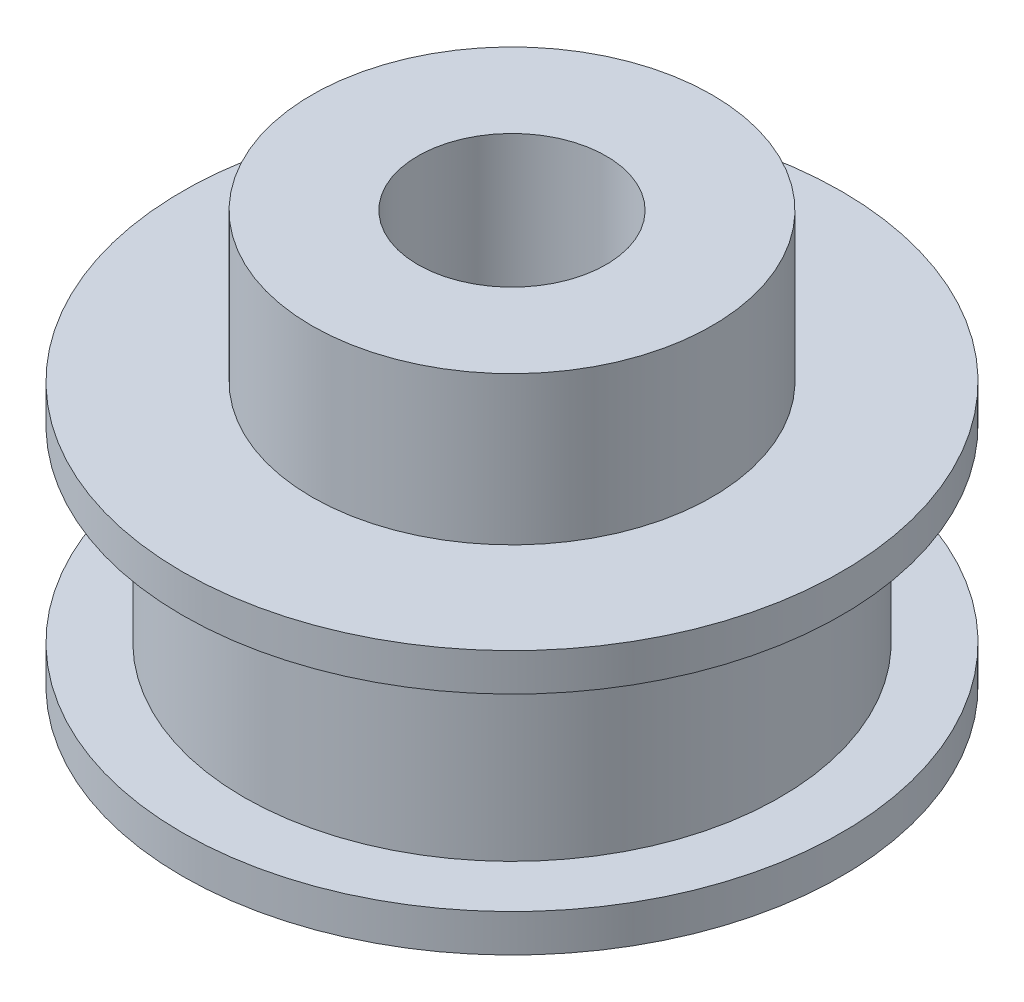
SolidWorks part; units mm, degrees
ref_plane "Front Plane" through (0, 0, 0) normal (0, 0, 1) x (1, 0, 0)
ref_plane "Top Plane" through (0, 0, 0) normal (0, 1, 0) x (1, 0, 0)
ref_plane "Right Plane" through (0, 0, 0) normal (1, 0, 0) x (0, 0, -1)
sketch "Sketch1" plane through (0, 0, 0) normal (0, 1, 0) x (1, 0, 0)
  circle A0 centre (0, 0) radius 11.39
  dimension "D1" = 22.78
extrude "Boss-Extrude1" add sketch "Sketch1" along normal blind 8
sketch "Sketch2" plane through (0, 8, 0) normal (0, 1, 0) x (1, 0, 0)
  circle A0 centre (0, 0) radius 14
  dimension "D1" = 28
extrude "Boss-Extrude2" add sketch "Sketch2" along normal blind 1.6
sketch "Sketch3" plane through (0, 9.6, 0) normal (0, 1, 0) x (1, 0, 0)
  circle A0 centre (0, 0) radius 8.5
extrude "Boss-Extrude3" add sketch "Sketch3" along normal blind 6.3
sketch "Sketch4" plane through (0, 15.9, 0) normal (0, 1, 0) x (1, 0, 0)
  circle A0 centre (0, 0) radius 4
extrude "Cut-Extrude1" cut sketch "Sketch4" against normal through all and the other way through all
sketch "Sketch5" plane through (0, 0, 0) normal (0, -1, 0) x (1, 0, 0)
  circle A0 centre (0, 0) radius 14
  circle A1 centre (0, 0) radius 4
extrude "Boss-Extrude4" add sketch "Sketch5" along normal blind 1.6
